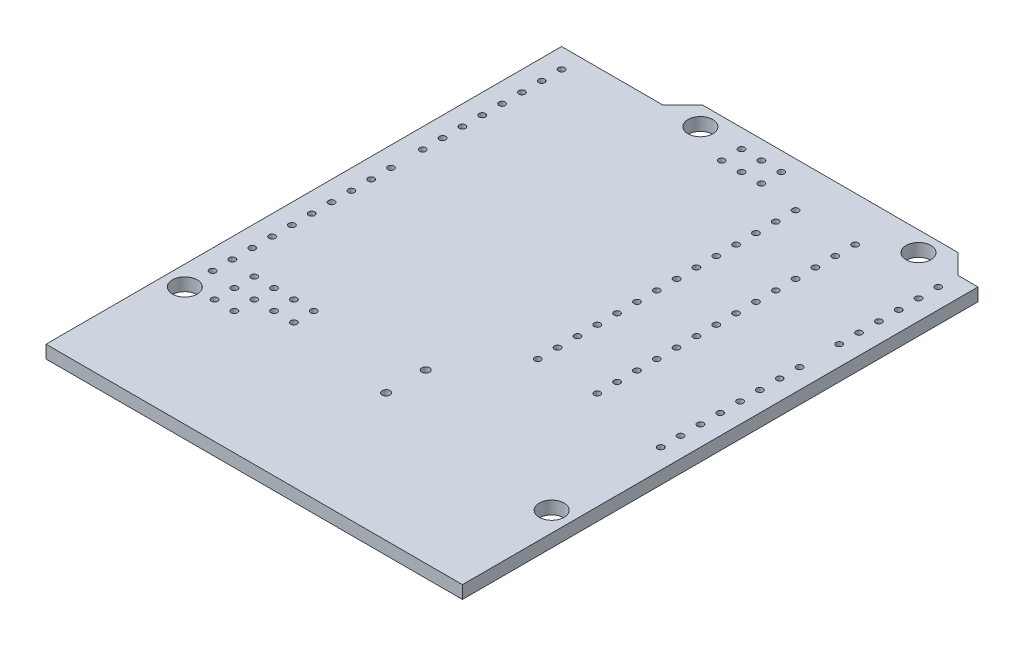
SolidWorks part; units mm, degrees
material "E-Glass Fiber"
ref_plane "Front Plane" through (0, 0, 0) normal (0, 0, 1) x (1, 0, 0)
ref_plane "Top Plane" through (0, 0, 0) normal (0, 1, 0) x (1, 0, 0)
ref_plane "Right Plane" through (0, 0, 0) normal (1, 0, 0) x (0, 0, -1)
sketch "Sketch1" plane through (0, 0, 0) normal (0, 1, 0) x (1, 0, 0)
  line L0 (-29.337, 0) -> (29.337, 0) construction
  line L1 (0, 0) -> (-53.34, 0)
  line L2 (0, 0) -> (0, 66.04)
  line L3 (-5.08, 68.58) -> (-37.846, 68.58)
  line L4 (-53.34, 0) -> (-53.34, 66.04)
  line L5 (-53.34, 66.04) -> (-40.386, 66.04)
  line L6 (-40.386, 66.04) -> (-37.846, 68.58)
  line L7 (-5.08, 68.58) -> (-2.54, 66.04)
  line L8 (-2.54, 66.04) -> (0, 66.04)
  circle A0 centre (-7.62, 66.04) radius 1.5875
  circle A1 centre (-35.56, 66.04) radius 1.5875
  circle A2 centre (-2.54, 13.97) radius 1.5875
  circle A3 centre (-50.8, 15.24) radius 1.5875
  dimension "D8" = 3.175
  dimension "D1" = 68.58
  dimension "D2" = 53.34
  dimension "D3" = 66.04
  dimension "D4" = 2.54
  dimension "D5" = 45
  dimension "D6" = 45
  dimension "D7" = 40.386
  dimension "D9" = 66.04
  dimension "D10" = 35.56
  dimension "D11" = 7.62
  dimension "D12" = 13.97
  dimension "D13" = 2.54
  dimension "D14" = 15.24
  dimension "D15" = 50.8
extrude "Boss-Extrude1" add sketch "Sketch1" against normal blind 1.65
sketch "Sketch2" plane through (0, 0, 0) normal (0, 1, 0) x (1, 0, 0)
  line L0 (0, -0.9075) -> (0, 0.9075) construction
  line L1 (-0.9075, 0) -> (0.9075, 0) construction
  circle A0 centre (-2.54, 27.94) radius 0.4
  dimension "D1" = 0.8
  dimension "D2" = 2.54
  dimension "D3" = 27.94
extrude "Cut-Extrude1" cut sketch "Sketch2" against normal blind 1.65
sketch "Sketch3" plane through (0, 0, 0) normal (0, 1, 0) x (1, 0, 0)
  line L0 (0, -0.9075) -> (0, 0.9075) construction
  line L1 (-0.9075, 0) -> (0.9075, 0) construction
  circle A0 centre (-50.8, 18.796) radius 0.4
  dimension "D2" = 0.8
  dimension "D1" = 50.8
  dimension "D3" = 18.796
extrude "Cut-Extrude2" cut sketch "Sketch3" against normal blind 1.65
pattern_linear "LPattern1" count 15 spacing 2.54 along (0, 0, -1) skipping (8, 0) of "Cut-Extrude1"
sketch "Sketch4" plane through (0, 0, 0) normal (0, 1, 0) x (1, 0, 0)
  line L0 (-0.9075, 0) -> (0.9075, 0) construction
  line L1 (0, -0.9075) -> (0, 0.9075) construction
  circle A0 centre (-50.8, 45.72) radius 0.4
  dimension "D3" = 0.8
  dimension "D1" = 45.72
  dimension "D2" = 50.8
extrude "Cut-Extrude3" cut sketch "Sketch4" against normal blind 1.65
pattern_linear "LPattern2" count 10 spacing 2.54 along (0, 0, -1) of "Cut-Extrude2"
pattern_linear "LPattern3" count 8 spacing 2.54 along (0, 0, -1) of "Cut-Extrude3"
sketch "Sketch5" plane through (0, 0, 0) normal (0, 1, 0) x (1, 0, 0)
  line L0 (-27.89, 66.18) -> (-27.89, 63.64) construction
  line L1 (-30.43, 66.18) -> (-25.35, 66.18) construction
  line L2 (-30.43, 66.18) -> (-30.43, 63.64) construction
  line L3 (-30.43, 63.64) -> (-25.35, 63.64) construction
  line L4 (-25.35, 66.18) -> (-25.35, 63.64) construction
  line L5 (-0.9075, 0) -> (0.9075, 0) construction
  line L6 (0, -0.9075) -> (0, 0.9075) construction
  circle A0 centre (-30.43, 66.18) radius 0.4
  circle A1 centre (-27.89, 66.18) radius 0.4
  circle A2 centre (-25.35, 66.18) radius 0.4
  circle A3 centre (-25.35, 63.64) radius 0.4
  circle A4 centre (-27.89, 63.64) radius 0.4
  circle A5 centre (-30.43, 63.64) radius 0.4
  circle A6 centre (-47.498, 15.748) radius 0.4
  circle A7 centre (-47.498, 18.288) radius 0.4
  circle A8 centre (-47.498, 20.828) radius 0.4
  circle A9 centre (-44.958, 20.828) radius 0.4
  circle A10 centre (-44.958, 18.288) radius 0.4
  circle A11 centre (-44.958, 15.748) radius 0.4
  circle A12 centre (-42.418, 18.288) radius 0.4
  circle A13 centre (-42.418, 20.828) radius 0.4
  circle A14 centre (-39.878, 20.828) radius 0.4
  circle A15 centre (-39.878, 18.288) radius 0.4
  circle A16 centre (-26.162, 21.463) radius 0.5
  circle A17 centre (-26.162, 16.383) radius 0.5
  dimension "D4" = 0.8
  dimension "D14" = 1
  dimension "D1" = 2.54
  dimension "D2" = 2.54
  dimension "D3" = 2.54
  dimension "D5" = 63.64
  dimension "D6" = 30.43
  dimension "D7" = 2.54
  dimension "D8" = 2.54
  dimension "D9" = 2.54
  dimension "D10" = 2.54
  dimension "D11" = 2.54
  dimension "D12" = 47.498
  dimension "D13" = 15.748
  dimension "D15" = 5.08
  dimension "D16" = 16.383
  dimension "D17" = 26.162
extrude "Cut-Extrude4" cut sketch "Sketch5" against normal blind 10
sketch "Sketch6" plane through (0, 0, 0) normal (0, 1, 0) x (1, 0, 0)
  line L0 (0, -0.9075) -> (0, 0.9075) construction
  line L1 (-0.9075, 0) -> (0.9075, 0) construction
  line L2 (-20.193, 29.845) -> (-20.193, 32.385) construction
  circle A0 centre (-20.193, 29.845) radius 0.4
  circle A1 centre (-12.573, 29.845) radius 0.4
  circle A2 centre (-20.193, 32.385) radius 0.4
  circle A3 centre (-12.573, 32.385) radius 0.4
  circle A4 centre (-20.193, 34.925) radius 0.4
  circle A5 centre (-12.573, 34.925) radius 0.4
  circle A6 centre (-20.193, 37.465) radius 0.4
  circle A7 centre (-12.573, 37.465) radius 0.4
  circle A8 centre (-20.193, 40.005) radius 0.4
  circle A9 centre (-12.573, 40.005) radius 0.4
  circle A10 centre (-20.193, 42.545) radius 0.4
  circle A11 centre (-12.573, 42.545) radius 0.4
  circle A12 centre (-20.193, 45.085) radius 0.4
  circle A13 centre (-12.573, 45.085) radius 0.4
  circle A14 centre (-20.193, 47.625) radius 0.4
  circle A15 centre (-12.573, 47.625) radius 0.4
  circle A16 centre (-20.193, 50.165) radius 0.4
  circle A17 centre (-12.573, 50.165) radius 0.4
  circle A18 centre (-20.193, 52.705) radius 0.4
  circle A19 centre (-12.573, 52.705) radius 0.4
  circle A20 centre (-20.193, 55.245) radius 0.4
  circle A21 centre (-12.573, 55.245) radius 0.4
  circle A22 centre (-20.193, 57.785) radius 0.4
  circle A23 centre (-12.573, 57.785) radius 0.4
  circle A24 centre (-20.193, 60.325) radius 0.4
  circle A25 centre (-12.573, 60.325) radius 0.4
  circle A26 centre (-20.193, 62.865) radius 0.4
  circle A27 centre (-12.573, 62.865) radius 0.4
  dimension "D1" = 0.8
  dimension "D2" = 7.62
  dimension "D3" = 12.573
  dimension "D4" = 29.845
  dimension "D6" = 2.54
  dimension "D5" = 14
extrude "Cut-Extrude5" cut sketch "Sketch6" against normal blind 10
sketch "Sketch7" plane through (0, 0, 0) normal (0, 1, 0) x (1, 0, 0)
  line L8 (0, 0) -> (0, 66.04)
  line L9 (0, 66.04) -> (-2.54, 66.04)
  line L10 (-2.54, 66.04) -> (-5.08, 68.58)
  line L11 (-5.08, 68.58) -> (-37.846, 68.58)
  line L12 (-37.846, 68.58) -> (-40.386, 66.04)
  line L13 (-40.386, 66.04) -> (-53.34, 66.04)
  line L14 (-53.34, 66.04) -> (-53.34, 0)
  line L15 (-53.34, 0) -> (0, 0)
  line L16 (0, 0) -> (0, 66.04)
  line L17 (0, 66.04) -> (-2.54, 66.04)
  line L18 (-2.54, 66.04) -> (-5.08, 68.58)
  line L19 (-5.08, 68.58) -> (-37.846, 68.58)
  line L20 (-37.846, 68.58) -> (-40.386, 66.04)
  line L21 (-40.386, 66.04) -> (-53.34, 66.04)
  line L22 (-53.34, 66.04) -> (-53.34, 0)
  line L23 (-53.34, 0) -> (0, 0)
  circle A0 centre (-50.8, 15.24) radius 1.5875 construction
  circle A1 centre (-2.54, 13.97) radius 1.5875 construction
  circle A2 centre (-7.62, 66.04) radius 1.5875 construction
  circle A3 centre (-35.56, 66.04) radius 1.5875 construction
  circle A4 centre (-50.8, 15.24) radius 1.5875
  circle A5 centre (-2.54, 13.97) radius 1.5875
  circle A6 centre (-7.62, 66.04) radius 1.5875
  circle A7 centre (-35.56, 66.04) radius 1.5875
  dimension "D1" = 0
equation "\"D13@Sketch5\"=0.001*25.4*620"
equation "\"D16@Sketch5\"=645*0.001*25.4"
